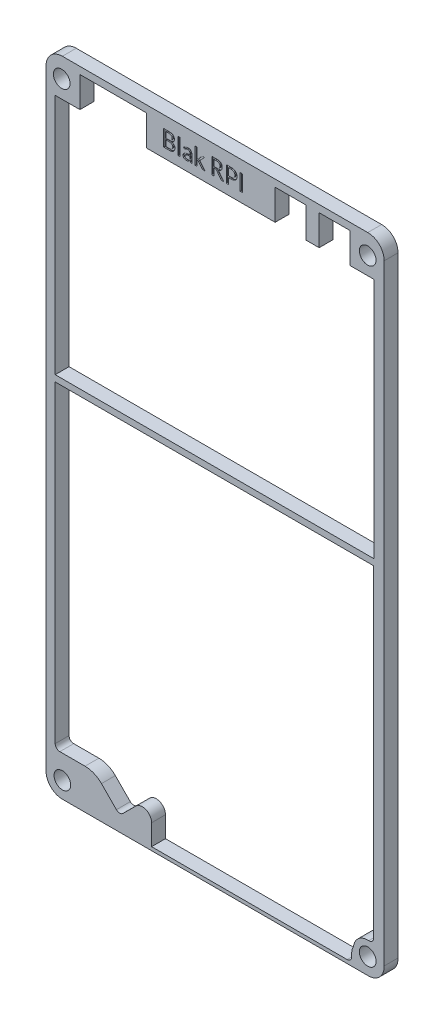
SolidWorks part; units mm, degrees
material "Plastique personnalisé"
ref_plane "Plan de face" through (0, 0, 0) normal (0, 0, 1) x (1, 0, 0)
ref_plane "Plan de dessus" through (0, 0, 0) normal (0, 1, 0) x (1, 0, 0)
ref_plane "Plan de droite" through (0, 0, 0) normal (1, 0, 0) x (0, 0, -1)
sketch "Model" plane through (0, 0, 0) normal (0, 0, 1) x (1, 0, 0)
  line L0 (60.325, -91.7751) -> (62.865, -91.7751) construction
  line L1 (62.865, -91.7751) -> (62.865, -89.2238) construction
  line L2 (60.325, -91.7751) -> (59.331, -91.7751) construction
  line L3 (59.331, -91.7751) -> (59.331, -223.8578) construction
  line L4 (62.865, -226.3838) -> (62.865, -227.3917) construction
  line L5 (62.865, -227.3917) -> (128.8982, -227.3917) construction
  line L6 (61.3167, -201.4361) -> (61.3167, -212.1957)
  line L7 (62.3167, -213.1957) -> (63.9379, -213.1957)
  line L8 (85.9453, -215.9539) -> (85.9453, -223.2248)
  line L9 (86.9453, -224.2248) -> (123.7097, -224.2248)
  line L10 (130.1941, -210.8644) -> (130.1941, -219.0967)
  line L11 (128.905, -223.8438) -> (128.905, -220.8492) construction
  line L12 (128.8982, -225.6398) -> (127.109, -223.8438) construction
  line L13 (130.701, -223.8438) -> (127.109, -223.8438) construction
  line L14 (61.0689, -223.8438) -> (64.6611, -223.8438) construction
  line L15 (130.1941, -219.0967) -> (130.1941, -219.7547)
  line L16 (123.7097, -224.2248) -> (124.8527, -224.2248)
  line L17 (60.96, -92.5438) -> (64.5521, -92.5438) construction
  line L18 (127.1089, -92.5438) -> (130.7011, -92.5438) construction
  line L23 (61.3167, -150.0154) -> (61.3167, -201.4361)
  line L27 (130.1941, -210.8644) -> (130.1941, -201.4361)
  line L28 (130.1941, -201.4361) -> (130.1941, -150.0154)
  line L29 (130.1941, -150.0154) -> (61.3167, -150.0154)
  line L32 (84.2382, -215.2468) -> (75.9713, -223.5137)
  line L33 (74.5531, -223.5096) -> (64.649, -213.4926)
  line L34 (108.9396, -89.764) -> (115.5172, -89.764)
  line L35 (115.5172, -89.764) -> (115.5172, -96.3404)
  line L36 (115.5172, -96.3404) -> (118.3946, -96.3404)
  line L37 (108.8806, -96.3404) -> (108.8806, -89.7625)
  line L38 (108.8806, -89.7625) -> (108.9396, -89.764)
  line L39 (118.4536, -89.7825) -> (125.0311, -89.7825)
  line L40 (125.0311, -89.7825) -> (125.0311, -96.3404)
  line L41 (125.0311, -96.3404) -> (130.21, -96.3404)
  line L42 (118.3946, -96.3404) -> (118.3946, -89.7811)
  line L43 (118.3946, -89.7811) -> (118.4536, -89.7825)
  line L44 (131.445, -223.8438) -> (132.4454, -223.8438) construction
  line L45 (132.4454, -223.8438) -> (132.4454, -91.7796) construction
  line L46 (128.905, -89.2238) -> (128.905, -88.2411)
  line L47 (128.905, -88.2411) -> (106.045, -88.2411)
  line L48 (62.865, -89.2238) -> (62.865, -88.2411) construction
  line L49 (62.865, -88.2411) -> (106.045, -88.2411) construction
  line L50 (106.045, -88.2411) -> (62.865, -88.2411)
  line L51 (59.331, -91.7751) -> (59.331, -223.8578)
  line L52 (62.865, -227.3917) -> (128.8982, -227.3917)
  line L53 (132.4454, -223.8438) -> (132.4454, -91.7796)
  line L54 (129.803, -90.9884) -> (132.7528, -87.6966) construction
  line L56 (61.3167, -148.6572) -> (130.21, -148.6572)
  line L57 (61.3167, -148.6572) -> (61.3167, -96.3404)
  line L58 (61.3167, -96.3404) -> (108.8806, -96.3404)
  line L59 (130.21, -148.6572) -> (130.21, -96.3404)
  arc A0 (128.905, -88.2411) -> (132.4454, -91.7796) centre (128.9896, -91.6969) cw
  arc A1 (59.331, -91.7751) -> (62.865, -88.2411) centre (62.865, -91.7751) cw
  arc A2 (59.331, -223.8578) -> (62.865, -227.3917) centre (62.865, -223.8578) ccw
  arc A3 (128.8982, -227.3917) -> (132.4454, -223.8438) centre (129.0305, -223.9768) ccw
  circle A4 centre (128.905, -223.8438) radius 1.8098
  circle A5 centre (62.865, -223.8438) radius 1.8
  arc A6 (129.1236, -220.7522) -> (125.8412, -223.3758) centre (128.905, -223.8438) ccw
  arc A7 (124.8527, -224.2248) -> (125.8412, -223.3758) centre (124.8527, -223.2248) ccw
  arc A8 (85.9453, -223.2248) -> (86.9453, -224.2248) centre (86.9453, -223.2248) ccw
  arc A9 (85.9453, -215.9539) -> (84.2382, -215.2468) centre (84.9453, -215.9539) ccw
  arc A10 (75.9713, -223.5137) -> (74.5531, -223.5096) centre (75.2642, -222.8065) cw
  arc A11 (63.9379, -213.1957) -> (64.649, -213.4926) centre (63.9379, -214.1957) cw
  arc A12 (61.3167, -212.1957) -> (62.3167, -213.1957) centre (62.3167, -212.1957) ccw
  arc A13 (130.1941, -219.7547) -> (129.1236, -220.7522) centre (129.1941, -219.7547) cw
  circle A14 centre (62.7216, -92.5438) radius 1.8
  circle A15 centre (128.8982, -92.5438) radius 1.8
  dimension "D1" = 1
  dimension "D2" = 1
extrude "Boss.-Extru.1" add sketch "Model" along normal blind 3
sketch "Esquisse2" plane through (15.4525, -0.5151, 3) normal (0, 0, 1) x (1, 0, 0)
  text T0 "Blak RPI" font "Lato" height 3.5
extrude "Enlèv. mat.-Extru.1" cut sketch "Esquisse2" against normal blind 0.25
sketch "Esquisse3" plane through (0, 0, 3) normal (0, 0, 1) x (1, 0, 0)
  line L0 (93.8018, -224.2248) -> (82.1626, -224.2248) construction
  line L1 (86.9453, -224.2248) -> (124.8527, -224.2248) construction
  line L2 (82.1626, -224.2248) -> (82.1626, -214.0076) construction
  line L4 (82.1626, -224.2248) -> (86.7519, -224.2248)
  line L5 (82.1626, -224.2248) -> (82.1626, -214.0775)
  line L6 (82.1626, -214.0775) -> (86.7519, -214.0775)
  line L7 (86.7519, -224.2248) -> (86.7519, -214.0775)
extrude "Enlèv. mat.-Extru.2" cut sketch "Esquisse3" against normal blind 10
sketch "Esquisse4" plane through (0, 0, 3) normal (0, 0, 1) x (1, 0, 0)
  line L1 (82.1626, -226.6328) -> (125.4454, -226.6328)
  line L2 (82.1626, -226.6328) -> (82.1626, -207.4323)
  line L3 (82.1626, -207.4323) -> (125.4454, -207.4323)
  line L4 (125.4454, -226.6328) -> (125.4454, -207.4323)
extrude "Enlèv. mat.-Extru.3" cut sketch "Esquisse4" against normal blind 10
sketch "Esquisse5" plane through (0, 0, 3) normal (0, 0, 1) x (1, 0, 0)
  line L0 (61.3167, -150.0154) -> (61.3167, -212.1957) construction
  line L1 (61.3167, -210.4519) -> (70.0285, -210.4519)
  line L2 (61.3167, -210.4519) -> (61.3167, -218.7567)
  line L3 (61.3167, -218.7567) -> (70.0285, -218.7567)
  line L4 (70.0285, -210.4519) -> (70.0285, -218.7567)
extrude "Enlèv. mat.-Extru.4" cut sketch "Esquisse5" against normal blind 10
fillet "Congé1" radius 5 1 edges at (69.8538, -218.7567, 1.5)
fillet "Congé2" radius 1 1 edges at (61.3167, -218.7567, 1.5)
fillet "Congé3" radius 2 1 edges at (82.1626, -217.3223, 1.5)
fillet "Congé4" radius 2 1 edges at (125.4454, -224.0302, 1.5)
fillet "Congé5" radius 1 1 edges at (125.4454, -226.6328, 1.5)
sketch "Esquisse6" plane through (0, 0, 3) normal (0, 0, 1) x (1, 0, 0)
  line L0 (108.8806, -89.7625) -> (39.6438, -89.7625) construction
  line L1 (61.3167, -96.3404) -> (108.8806, -96.3404) construction
  line L2 (66.664, -89.7625) -> (81.0944, -89.7625)
  line L3 (66.664, -89.7625) -> (66.664, -96.3404)
  line L4 (66.664, -96.3404) -> (81.0944, -96.3404)
  line L5 (81.0944, -89.7625) -> (81.0944, -96.3404)
extrude "Enlèv. mat.-Extru.5" cut sketch "Esquisse6" against normal blind 10
